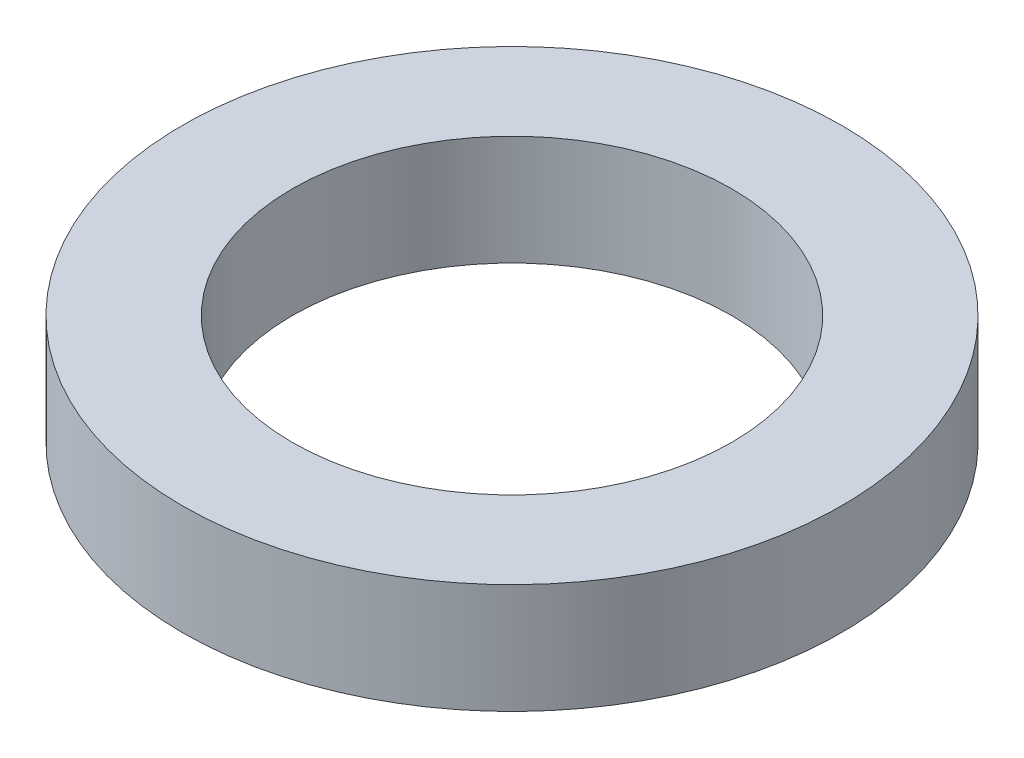
SolidWorks part; units mm, degrees
material "1.5714 (16NiCr4)"
ref_plane "Спереди" through (0, 0, 0) normal (0, 0, 1) x (1, 0, 0)
ref_plane "Сверху" through (0, 0, 0) normal (0, 1, 0) x (1, 0, 0)
ref_plane "Справа" through (0, 0, 0) normal (1, 0, 0) x (0, 0, -1)
sketch "Эскиз1" plane through (0, 0, 0) normal (0, 1, 0) x (1, 0, 0)
  circle A0 centre (0, 0) radius 6
  circle A1 centre (0, 0) radius 4
extrude "Бобышка-Вытянуть1" add sketch "Эскиз1" along normal blind 2
